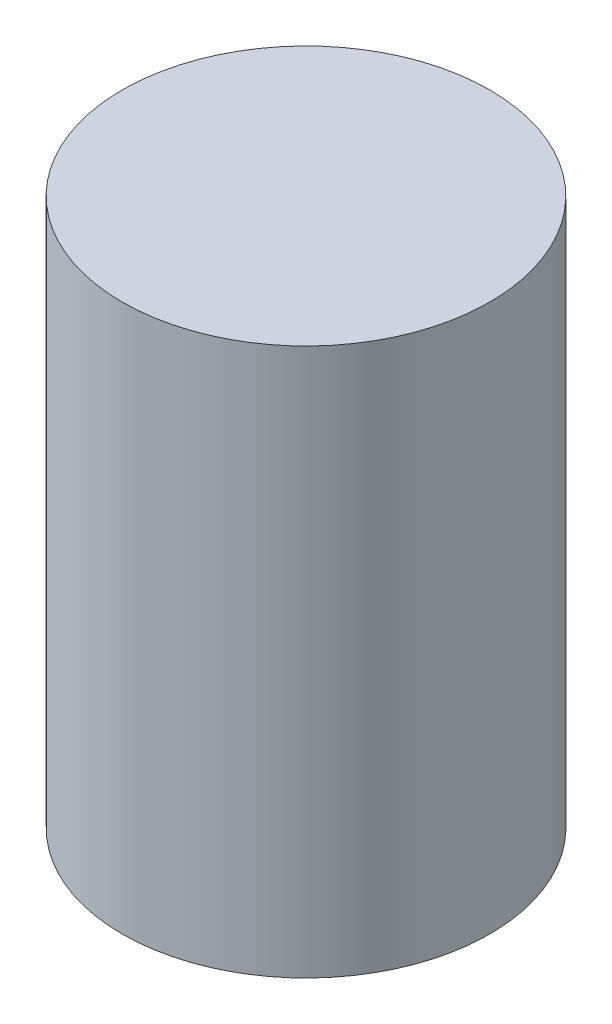
SolidWorks part; units mm, degrees
ref_plane "Front Plane" through (0, 0, 0) normal (0, 0, 1) x (1, 0, 0)
ref_plane "Top Plane" through (0, 0, 0) normal (0, 1, 0) x (1, 0, 0)
ref_plane "Right Plane" through (0, 0, 0) normal (1, 0, 0) x (0, 0, -1)
sketch "Sketch1" plane through (0, 0, 0) normal (0, 1, 0) x (1, 0, 0)
  circle A0 centre (0, 0) radius 2.35
  dimension "D1" = 4.7
extrude "Boss-Extrude1" add sketch "Sketch1" along normal blind 7
